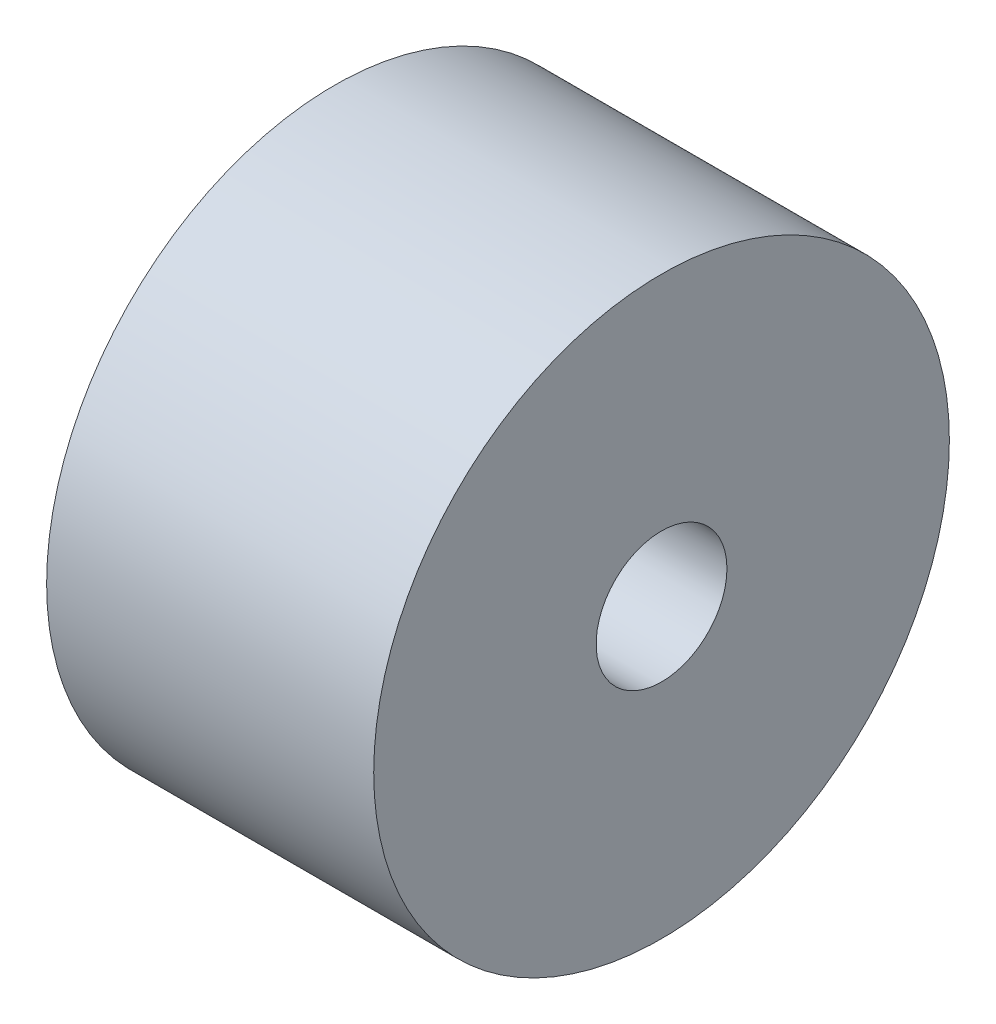
SolidWorks part; units mm, degrees
ref_plane "Спереди" through (0, 0, 0) normal (0, 0, 1) x (1, 0, 0)
ref_plane "Сверху" through (0, 0, 0) normal (0, 1, 0) x (1, 0, 0)
ref_plane "Справа" through (0, 0, 0) normal (1, 0, 0) x (0, 0, -1)
sketch "Эскиз1" plane through (0, 0, 0) normal (1, 0, 0) x (0, 0, -1)
  circle A0 centre (0, 0) radius 1
  circle A1 centre (0, 0) radius 4.4
  dimension "D1" = 2
  dimension "D2" = 8.8
extrude "Бобышка-Вытянуть1" add sketch "Эскиз1" along normal blind 5
